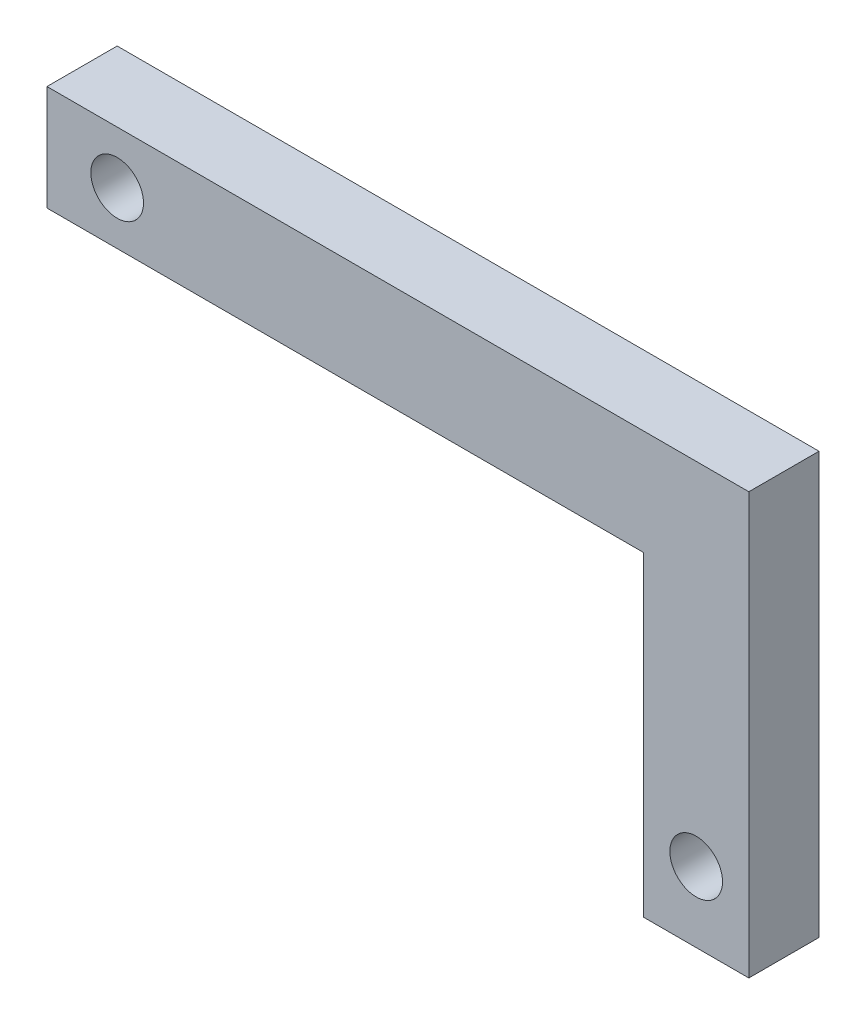
SolidWorks part; units mm, degrees
material "Pine"
ref_plane "Front Plane" through (0, 0, 0) normal (0, 0, 1) x (1, 0, 0)
ref_plane "Top Plane" through (0, 0, 0) normal (0, 1, 0) x (1, 0, 0)
ref_plane "Right Plane" through (0, 0, 0) normal (1, 0, 0) x (0, 0, -1)
sketch "Sketch1" plane through (0, 0, 0) normal (0, 0, 1) x (1, 0, 0)
  line L1 (0, 0) -> (254, 0)
  line L2 (0, 0) -> (0, 38.1)
  line L3 (0, 38.1) -> (254, 38.1)
  line L4 (254, 0) -> (254, 38.1)
  line L5 (254, 0) -> (215.9, 0)
  line L6 (254, 0) -> (254, -114.3)
  line L7 (254, -114.3) -> (215.9, -114.3)
  line L8 (215.9, 0) -> (215.9, -114.3)
  dimension "D1" = 254
  dimension "D2" = 38.1
  dimension "D3" = 114.3
  dimension "D4" = 38.1
extrude "Boss-Extrude1" add sketch "Sketch1" along normal blind 25.4 contours L1 L4 L3 L2 | L1 L8 L7 L6
sketch "Sketch2" plane through (0, 0, 25.4) normal (0, 0, 1) x (1, 0, 0)
  line L0 (0, 0) -> (0, 38.1) construction
  line L1 (0, 0) -> (215.9, 0) construction
  circle A0 centre (25.4, 19.05) radius 9.525
  dimension "D1" = 19.05
  dimension "D2" = 25.4
  dimension "D3" = 19.05
extrude "Cut-Extrude1" cut sketch "Sketch2" against normal through all
sketch "Sketch3" plane through (0, 0, 25.4) normal (0, 0, 1) x (1, 0, 0)
  line L0 (254, -114.3) -> (254, 38.1) construction
  line L1 (254, -114.3) -> (215.9, -114.3) construction
  circle A0 centre (234.95, -88.9) radius 9.525
  dimension "D1" = 19.05
  dimension "D2" = 19.05
  dimension "D3" = 25.4
extrude "Cut-Extrude2" cut sketch "Sketch3" against normal through all
